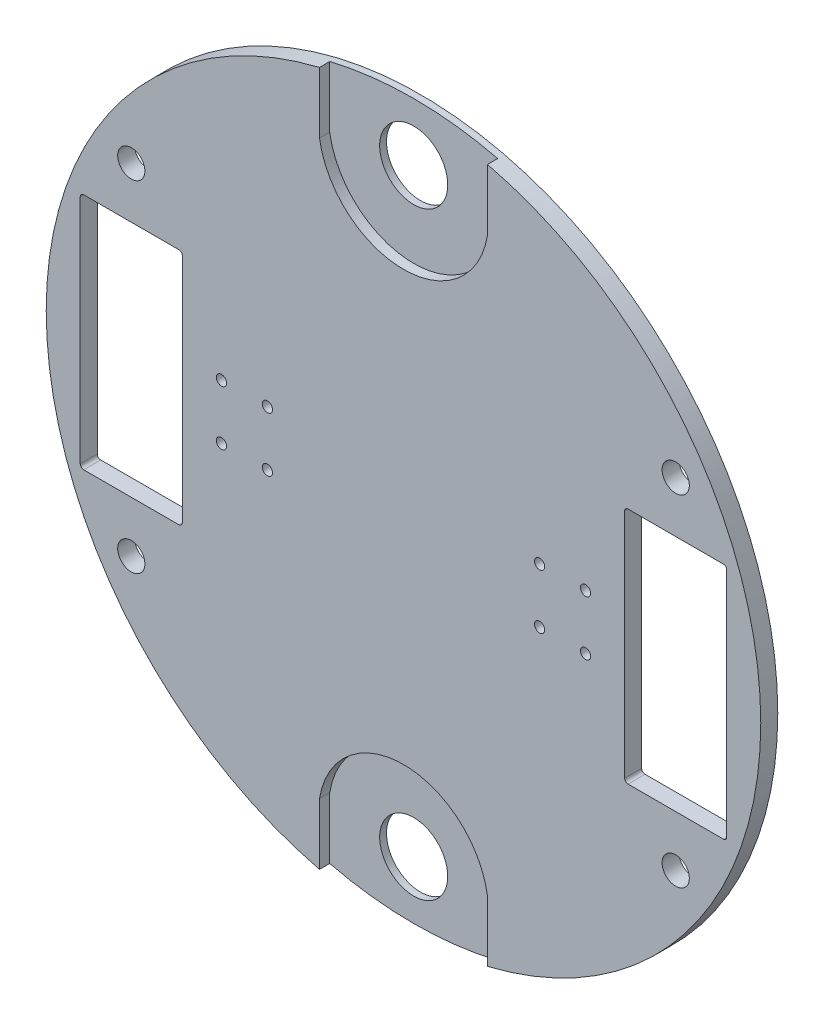
SolidWorks part; units mm, degrees
material "Polyéthylène réticulé"
ref_plane "Plan de face" through (0, 0, 0) normal (0, 0, 1) x (1, 0, 0)
ref_plane "Plan de dessus" through (0, 0, 0) normal (0, 1, 0) x (1, 0, 0)
ref_plane "Plan de droite" through (0, 0, 0) normal (1, 0, 0) x (0, 0, -1)
sketch "Esquisse1" plane through (0, 0, 0) normal (0, 0, 1) x (1, 0, 0)
  line L0 (0, 113.8712) -> (0, -130.9268) construction
  line L1 (-95, 35) -> (-65, 35)
  line L2 (-95, 35) -> (-95, -35)
  line L3 (-95, -35) -> (-65, -35)
  line L4 (-65, 35) -> (-65, -35)
  line L5 (-95, 35) -> (-65, -35) construction
  line L6 (-95, -35) -> (-65, 35) construction
  line L7 (95, -35) -> (65, -35)
  line L8 (65, 35) -> (65, -35)
  line L9 (95, 35) -> (95, -35)
  line L10 (95, 35) -> (65, 35)
  line L11 (-121.3457, 0) -> (123.2263, 0) construction
  circle A0 centre (0, 0) radius 105
  circle A1 centre (-80, 50) radius 4
  circle A2 centre (80, 50) radius 4
  circle A3 centre (80, -50) radius 4
  circle A4 centre (-80, -50) radius 4
  point P3 (-80, 0)
  dimension "D1" = 210
  dimension "D5" = 8
  dimension "D2" = 70
  dimension "D3" = 80
  dimension "D4" = 30
  dimension "D6" = 80
  dimension "D7" = 50
extrude "Boss.-Extru.1" add sketch "Esquisse1" along normal blind 5
sketch "Esquisse2" plane through (0, 0, 5) normal (0, 0, 1) x (1, 0, 0)
  line L0 (-65, -35) -> (-65, 35) construction
  line L1 (-65, 35) -> (-95, 35) construction
  line L2 (0, 50.5769) -> (0, -43.3399) construction
  circle A12 centre (-53.5, -8.0429) radius 1.5
  circle A13 centre (-40, -8.0429) radius 1.5
  circle A14 centre (-53.5, 8.0429) radius 1.5
  circle A15 centre (-40, 8.0429) radius 1.5
  circle A16 centre (40, 8.0429) radius 1.5
  circle A17 centre (53.5, 8.0429) radius 1.5
  circle A18 centre (40, -8.0429) radius 1.5
  circle A19 centre (53.5, -8.0429) radius 1.5
  dimension "D2" = 3
  dimension "D3" = 3
  dimension "D4" = 3
  dimension "D5" = 3
  dimension "D1" = 11.5
  dimension "D6" = 26.9571
  dimension "D7" = 16.0857
  dimension "D8" = 13.5
extrude "Enlèv. mat.-Extru.1" cut sketch "Esquisse2" against normal through all
fillet "Congé1" radius 1 8 edges at (65, -35, 2.5) (95, -35, 2.5) (95, 35, 2.5) (65, 35, 2.5) (-65, -35, 2.5) (-95, -35, 2.5) (-65, 35, 2.5) (-95, 35, 2.5)
sketch "Esquisse3" plane through (0, 0, 5) normal (0, 0, 1) x (1, 0, 0)
  line L0 (-24.687, -84.0566) -> (-24.687, -102.0566)
  line L1 (24.687, -84.0566) -> (24.687, -102.0566)
  line L2 (-56.4287, 0) -> (132.5603, 0) construction
  line L3 (24.687, 84.0566) -> (24.687, 102.0566)
  line L4 (-24.687, 84.0566) -> (-24.687, 102.0566)
  circle A0 centre (0, 0) radius 105 construction
  circle A1 centre (0, 0) radius 105
  arc A2 (-24.687, -84.0566) -> (24.687, -84.0566) centre (0, -88) cw
  arc A3 (-24.687, 84.0566) -> (24.687, 84.0566) centre (0, 88) ccw
  circle M12 centre (0, 0) radius 105
  dimension "D1" = 25
  dimension "D2" = 18
  dimension "D3" = 88
extrude "Enlèv. mat.-Extru.2" cut sketch "Esquisse3" against normal blind 3 contours L4 A3 L3 M12 | A2 L0 L1 M12
sketch "Esquisse4" plane through (0, 0, 5) normal (0, 0, 1) x (1, 0, 0)
  arc A0 (-24.687, 84.0566) -> (24.687, 84.0566) centre (0, 88) ccw construction
  arc A1 (24.687, -84.0566) -> (-24.687, -84.0566) centre (0, -88) ccw construction
  arc A2 (-24.687, 84.0566) -> (24.687, 84.0566) centre (0, 88) ccw
  arc A3 (24.687, -84.0566) -> (-24.687, -84.0566) centre (0, -88) ccw
  circle A4 centre (0, -88) radius 10
  circle A5 centre (0, 88) radius 10
  dimension "D1" = 20
  dimension "D2" = 20
extrude "Enlèv. mat.-Extru.3" cut sketch "Esquisse4" against normal through all contours A5 | A4
